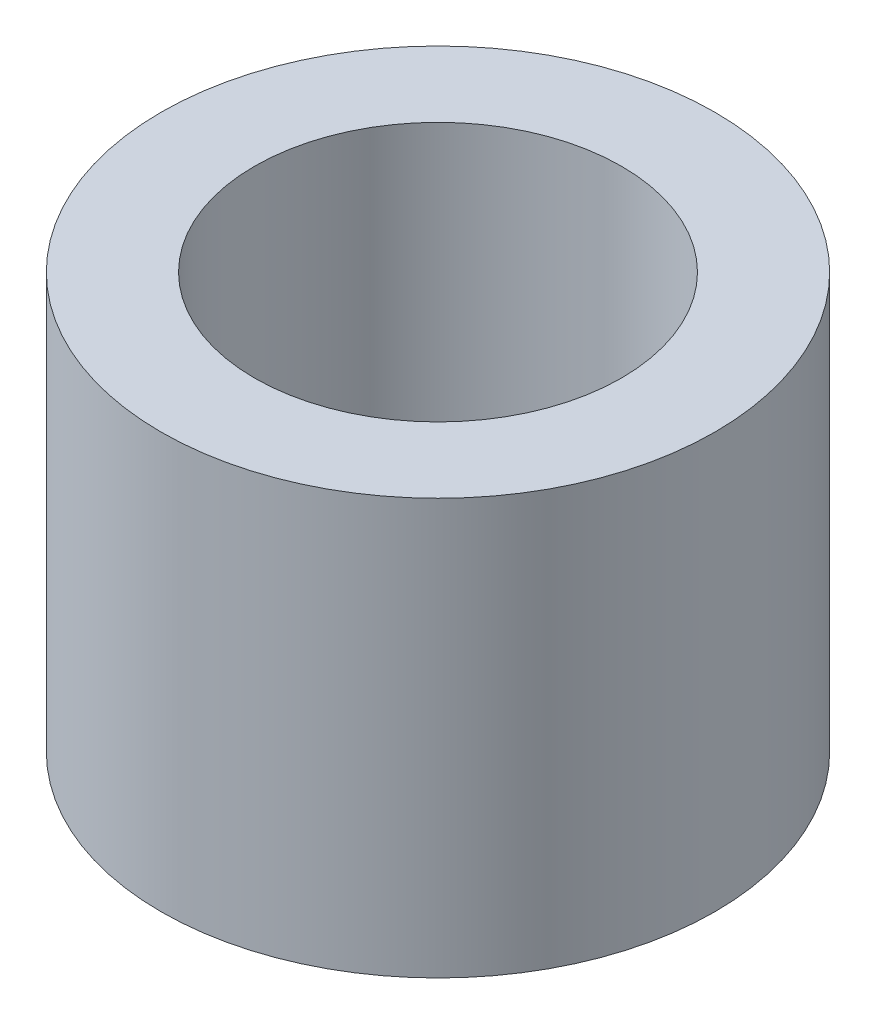
SolidWorks part; units mm, degrees
ref_plane "Top Plane" through (0, 0, 0) normal (0, 0, 1) x (1, 0, 0)
ref_plane "Front Plane" through (0, 0, 0) normal (0, 1, 0) x (1, 0, 0)
ref_plane "Right Plane" through (0, 0, 0) normal (1, 0, 0) x (0, 0, -1)
sketch "Sketch1" plane through (0, 0, 0) normal (0, 1, 0) x (1, 0, 0)
  circle A0 centre (0, 0) radius 4
  circle A1 centre (0, 0) radius 2.65
  dimension "D1" = 8
  dimension "D2" = 5.3
extrude "Boss-Extrude1" add sketch "Sketch1" along normal blind 6
